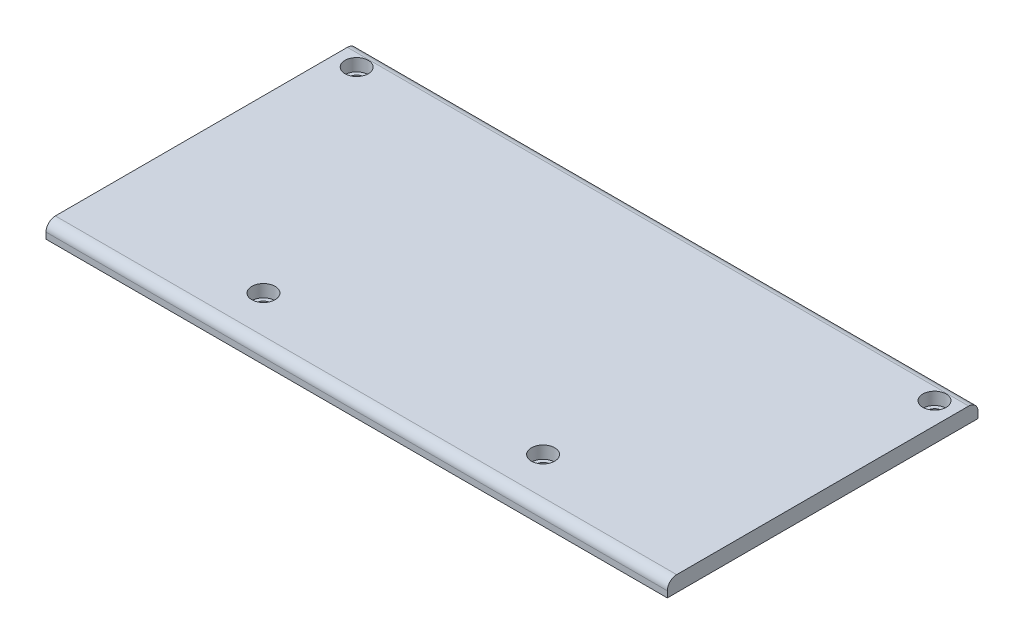
SolidWorks part; units mm, degrees
ref_plane "Front Plane" through (0, 0, 0) normal (0, 0, 1) x (1, 0, 0)
ref_plane "Top Plane" through (0, 0, 0) normal (0, 1, 0) x (1, 0, 0)
ref_plane "Right Plane" through (0, 0, 0) normal (1, 0, 0) x (0, 0, -1)
sketch "Sketch1" plane through (0, 0, 0) normal (0, 1, 0) x (1, 0, 0)
  line L0 (0, 0) -> (-51684.5009, 0) construction
  line L1 (0, 0) -> (0, -51684.5009) construction
  line L3 (-100, 50) -> (100, 50)
  line L4 (-100, 50) -> (-100, -50)
  line L5 (-100, -50) -> (100, -50)
  line L6 (100, 50) -> (100, -50)
  line L7 (-100, 50) -> (100, -50) construction
  line L8 (-100, -50) -> (100, 50) construction
  point P5 (0, 0)
  dimension "D1" = 200
  dimension "D2" = 100
extrude "Boss-Extrude1" add sketch "Sketch1" along normal blind 5
sketch "Sketch2" plane through (0, 5, 0) normal (0, 1, 0) x (1, 0, 0)
  line L0 (0, 0) -> (-50000, 0) construction
  line L1 (0, 0) -> (0, -50000) construction
  line L2 (100, 50) -> (-100, 50) construction
  line L3 (-100, 50) -> (-100, -50) construction
  line L4 (-100, -50) -> (100, -50) construction
  circle A0 centre (-93, 43) radius 2.5
  circle A1 centre (-45, -35) radius 2.5
  circle A2 centre (93, 43) radius 2.5
  circle A3 centre (45, -35) radius 2.5
  dimension "D1" = 5
  dimension "D2" = 7
  dimension "D3" = 7
  dimension "D4" = 5
  dimension "D5" = 45
  dimension "D6" = 15
extrude "Cut-Extrude1" cut sketch "Sketch2" against normal through all
sketch "Sketch3" plane through (0, 5, 0) normal (0, 1, 0) x (1, 0, 0)
  line L1 (0, 0) -> (-50000, 0) construction
  line L2 (0, 0) -> (0, -50000) construction
  circle A0 centre (-93, 43) radius 3.75
  circle A1 centre (-45, -35) radius 3.75
  circle A2 centre (45, -35) radius 3.75
  circle A3 centre (93, 43) radius 3.75
  dimension "D1" = 7.5
  dimension "D2" = 7.5
extrude "Cut-Extrude2" cut sketch "Sketch3" against normal blind 4
fillet "Fillet1" radius 3 2 edges at (0, 5, 50) (0, 5, -50)
